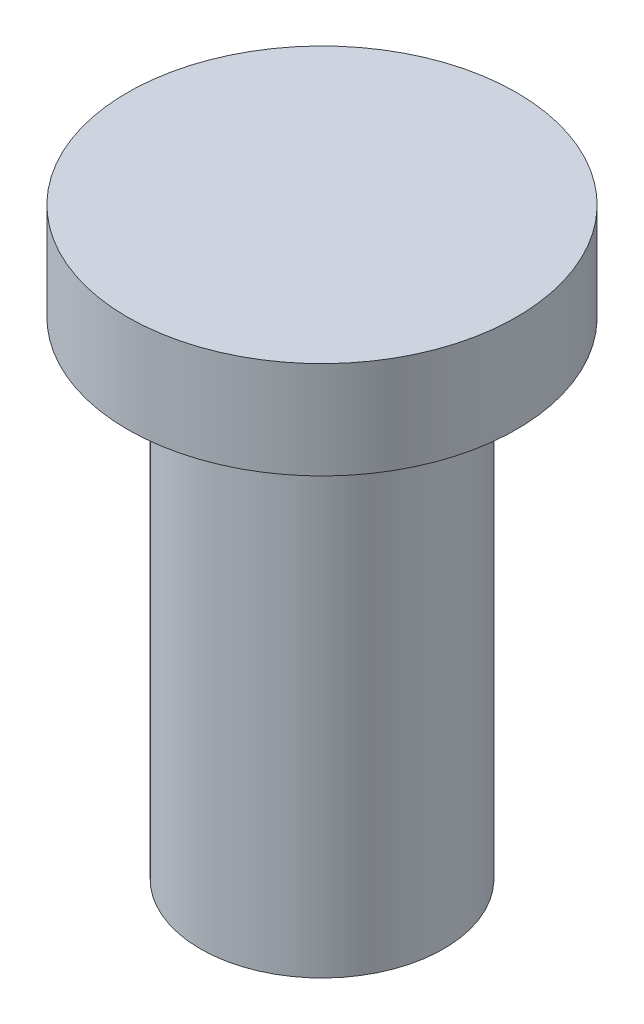
SolidWorks part; units mm, degrees
ref_plane "Front Plane" through (0, 0, 0) normal (0, 0, 1) x (1, 0, 0)
ref_plane "Top Plane" through (0, 0, 0) normal (0, 1, 0) x (1, 0, 0)
ref_plane "Right Plane" through (0, 0, 0) normal (1, 0, 0) x (0, 0, -1)
sketch "Sketch1" plane through (0, 0, 0) normal (0, 1, 0) x (1, 0, 0)
  circle A0 centre (0, 0) radius 1.25
extrude "Boss-Extrude1" add sketch "Sketch1" along normal blind 5
sketch "Sketch2" plane through (0, 5, 0) normal (0, 1, 0) x (1, 0, 0)
  circle A0 centre (0, 0) radius 2
extrude "Boss-Extrude2" add sketch "Sketch2" along normal blind 1
